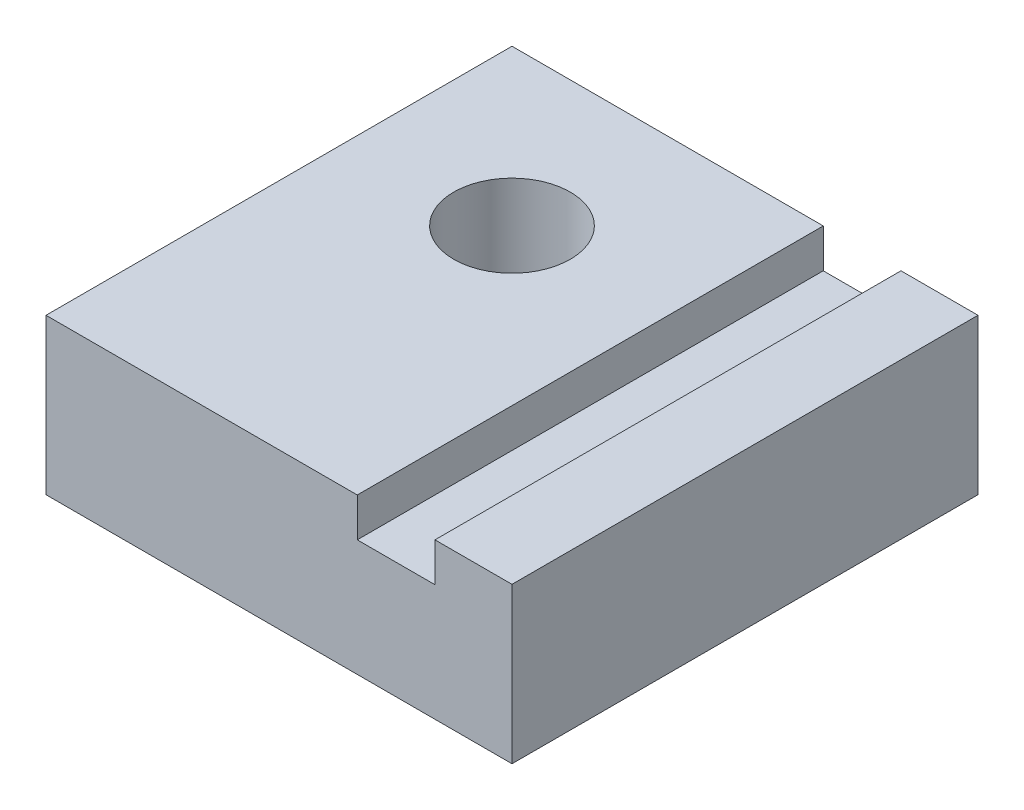
SolidWorks part; units mm, degrees
ref_plane "Front Plane" through (0, 0, 0) normal (0, 0, 1) x (1, 0, 0)
ref_plane "Top Plane" through (0, 0, 0) normal (0, 1, 0) x (1, 0, 0)
ref_plane "Right Plane" through (0, 0, 0) normal (1, 0, 0) x (0, 0, -1)
sketch "Sketch1" plane through (0, 0, 0) normal (0, 1, 0) x (1, 0, 0)
  line L1 (-38.078, -38.078) -> (38.078, -38.078)
  line L2 (-38.078, -38.078) -> (-38.078, 38.078)
  line L3 (-38.078, 38.078) -> (38.078, 38.078)
  line L4 (38.078, -38.078) -> (38.078, 38.078)
  line L5 (-38.078, -38.078) -> (38.078, 38.078) construction
  line L6 (-38.078, 38.078) -> (38.078, -38.078) construction
  circle A0 centre (-12.678, 12.678) radius 9.525
  point P0 (0, 0)
extrude "Boss-Extrude1" add sketch "Sketch1" along normal blind 25.4
sketch "Sketch2" plane through (0, 0, 38.078) normal (0, 0, 1) x (1, 0, 0)
  line L5 (25.4894, 25.4) -> (12.7894, 25.4)
  line L6 (25.4894, 25.4) -> (25.4894, 19.05)
  line L7 (25.4894, 19.05) -> (12.7894, 19.05)
  line L8 (12.7894, 25.4) -> (12.7894, 19.05)
extrude "Cut-Extrude1" cut sketch "Sketch2" against normal through all
